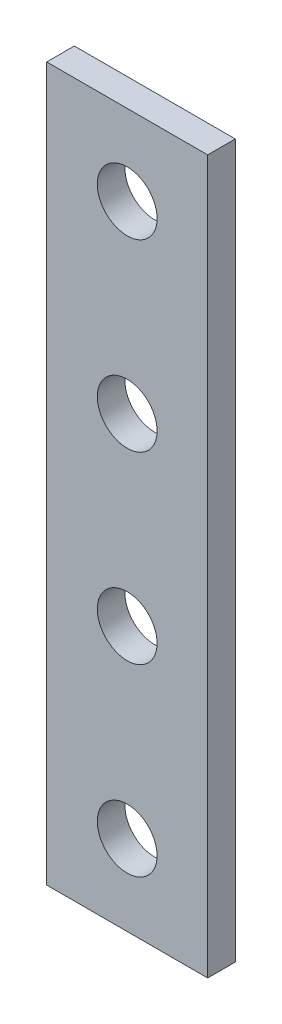
SolidWorks part; units mm, degrees
ref_plane "前视基准面" through (0, 0, 0) normal (0, 0, 1) x (1, 0, 0)
ref_plane "上视基准面" through (0, 0, 0) normal (0, 1, 0) x (1, 0, 0)
ref_plane "右视基准面" through (0, 0, 0) normal (1, 0, 0) x (0, 0, -1)
sketch "草图1" plane through (0, 0, 0) normal (0, 0, 1) x (1, 0, 0)
  line L1 (-35, 155) -> (35, 155)
  line L2 (-35, 155) -> (-35, -155)
  line L3 (-35, -155) -> (35, -155)
  line L4 (35, 155) -> (35, -155)
  line L5 (-35, 155) -> (35, -155) construction
  line L6 (-35, -155) -> (35, 155) construction
  point P0 (0, 0)
extrude "凸台-拉伸1" add sketch "草图1" along normal blind 12
sketch "草图2" plane through (0, 0, 12) normal (0, 0, 1) x (1, 0, 0)
  line L0 (-35, 120) -> (35, 120) construction
  line L1 (-35, 155) -> (-35, -155) construction
  line L2 (35, -155) -> (35, 155) construction
  line L3 (35, 155) -> (-35, 155) construction
  line L4 (0, 155) -> (0, -155) construction
  line L5 (-35, -155) -> (35, -155) construction
  circle A0 centre (0, 120) radius 13
  dimension "D1" = 35
  dimension "D2" = 35
extrude "切除-拉伸1" cut sketch "草图2" against normal through all
pattern_linear "阵列(线性)1" count 4 spacing 80 along (0, -1, 0) of "切除-拉伸1"
